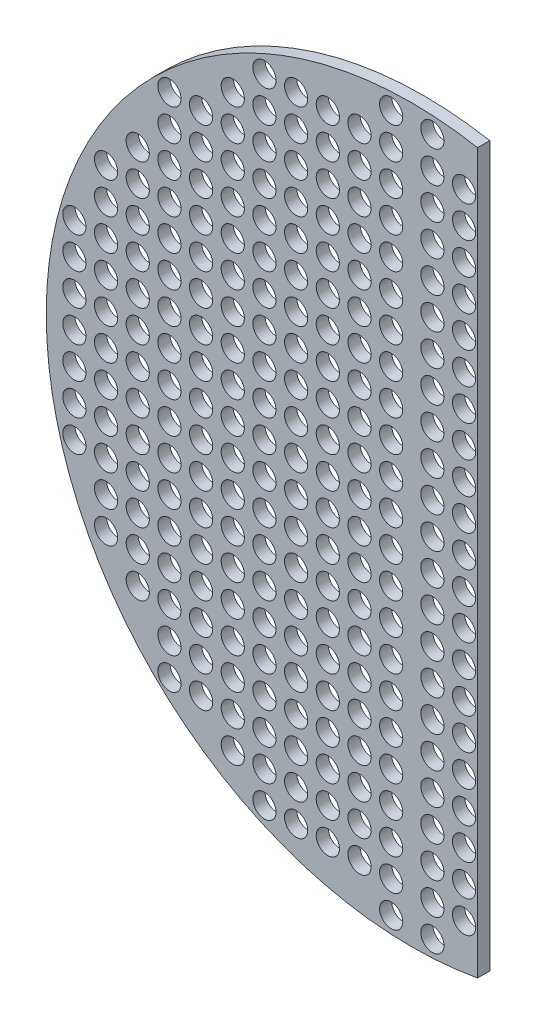
SolidWorks part; units mm, degrees
material " 12Х18Н10Т ГОСТ 4543-71"
ref_plane "Спереди" through (0, 0, 0) normal (0, 0, 1) x (1, 0, 0)
ref_plane "Сверху" through (0, 0, 0) normal (0, 1, 0) x (1, 0, 0)
ref_plane "Справа" through (0, 0, 0) normal (1, 0, 0) x (0, 0, -1)
sketch "Эскиз1" plane through (0, 0, 0) normal (0, 0, 1) x (1, 0, 0)
  circle A0 centre (0, 0) radius 300
  dimension "D1" = 600
extrude "Бобышка-Вытянуть1" add sketch "Эскиз1" along normal mid plane 10
sketch "Sketch1" plane through (0, 0, 5) normal (0, 0, 1) x (1, 0, 0)
  line L1 (0, 0) -> (0, -73.9638) construction
  line L2 (3.9158, 0) -> (0, 0) construction
  line L3 (0, 0) -> (29.9158, 0) construction
  circle A0 centre (16.9158, 0) radius 9.525
  circle A1 centre (42.9158, 0) radius 9.525
  circle A11 centre (42.9158, 0) radius 9.525
  circle A21 centre (42.9158, 26) radius 9.525
  circle A31 centre (42.9158, 52) radius 9.525
  circle A41 centre (42.9158, 78) radius 9.525
  circle A51 centre (42.9158, 104) radius 9.525
  circle A60 centre (16.9158, -286) radius 9.525
  circle A61 centre (42.9158, 130) radius 9.525
  circle A70 centre (16.9158, -260) radius 9.525
  circle A71 centre (42.9158, 156) radius 9.525
  circle A79 centre (16.9158, -234) radius 9.525
  circle A80 centre (16.9158, -208) radius 9.525
  circle A81 centre (42.9158, 182) radius 9.525
  circle A88 centre (16.9158, -182) radius 9.525
  circle A89 centre (16.9158, -156) radius 9.525
  circle A90 centre (16.9158, -130) radius 9.525
  circle A91 centre (42.9158, 208) radius 9.525
  circle A98 centre (16.9158, -104) radius 9.525
  circle A99 centre (16.9158, -78) radius 9.525
  circle A100 centre (16.9158, -52) radius 9.525
  circle A101 centre (42.9158, 234) radius 9.525
  circle A106 centre (16.9158, -26) radius 9.525
  circle A110 centre (42.9158, -260) radius 9.525
  circle A111 centre (42.9158, 260) radius 9.525
  circle A119 centre (42.9158, -234) radius 9.525
  circle A126 centre (42.9158, -208) radius 9.525
  circle A131 centre (16.9158, 26) radius 9.525
  circle A132 centre (16.9158, 52) radius 9.525
  circle A133 centre (16.9158, 78) radius 9.525
  circle A134 centre (16.9158, 104) radius 9.525
  circle A135 centre (16.9158, 130) radius 9.525
  circle A136 centre (16.9158, 156) radius 9.525
  circle A137 centre (16.9158, 182) radius 9.525
  circle A138 centre (16.9158, 208) radius 9.525
  circle A139 centre (16.9158, 234) radius 9.525
  circle A140 centre (16.9158, 260) radius 9.525
  circle A141 centre (16.9158, 286) radius 9.525
  circle A144 centre (42.9158, -182) radius 9.525
  circle A152 centre (42.9158, -156) radius 9.525
  circle A161 centre (42.9158, -130) radius 9.525
  circle A170 centre (42.9158, -104) radius 9.525
  circle A180 centre (42.9158, -78) radius 9.525
  circle A190 centre (42.9158, -52) radius 9.525
  circle A200 centre (42.9158, -26) radius 9.525
  circle A201 centre (-42.9158, -26) radius 9.525
  circle A202 centre (-68.9158, -26) radius 9.525
  circle A203 centre (-94.9158, -26) radius 9.525
  circle A204 centre (-120.9158, -26) radius 9.525
  circle A205 centre (-146.9158, -26) radius 9.525
  circle A206 centre (-172.9158, -26) radius 9.525
  circle A207 centre (-198.9158, -26) radius 9.525
  circle A208 centre (-224.9158, -26) radius 9.525
  circle A209 centre (-250.9158, -26) radius 9.525
  circle A210 centre (-276.9158, -26) radius 9.525
  circle A211 centre (-42.9158, -52) radius 9.525
  circle A212 centre (-68.9158, -52) radius 9.525
  circle A213 centre (-94.9158, -52) radius 9.525
  circle A214 centre (-120.9158, -52) radius 9.525
  circle A215 centre (-146.9158, -52) radius 9.525
  circle A216 centre (-172.9158, -52) radius 9.525
  circle A217 centre (-198.9158, -52) radius 9.525
  circle A218 centre (-224.9158, -52) radius 9.525
  circle A219 centre (-250.9158, -52) radius 9.525
  circle A220 centre (-276.9158, -52) radius 9.525
  circle A221 centre (-42.9158, -78) radius 9.525
  circle A222 centre (-68.9158, -78) radius 9.525
  circle A223 centre (-94.9158, -78) radius 9.525
  circle A224 centre (-120.9158, -78) radius 9.525
  circle A225 centre (-146.9158, -78) radius 9.525
  circle A226 centre (-172.9158, -78) radius 9.525
  circle A227 centre (-198.9158, -78) radius 9.525
  circle A228 centre (-224.9158, -78) radius 9.525
  circle A229 centre (-250.9158, -78) radius 9.525
  circle A230 centre (-276.9158, -78) radius 9.525
  circle A231 centre (-42.9158, -104) radius 9.525
  circle A232 centre (-68.9158, -104) radius 9.525
  circle A233 centre (-94.9158, -104) radius 9.525
  circle A234 centre (-120.9158, -104) radius 9.525
  circle A235 centre (-146.9158, -104) radius 9.525
  circle A236 centre (-172.9158, -104) radius 9.525
  circle A237 centre (-198.9158, -104) radius 9.525
  circle A238 centre (-224.9158, -104) radius 9.525
  circle A239 centre (-250.9158, -104) radius 9.525
  circle A240 centre (-42.9158, -130) radius 9.525
  circle A241 centre (-68.9158, -130) radius 9.525
  circle A242 centre (-94.9158, -130) radius 9.525
  circle A243 centre (-120.9158, -130) radius 9.525
  circle A244 centre (-146.9158, -130) radius 9.525
  circle A245 centre (-172.9158, -130) radius 9.525
  circle A246 centre (-198.9158, -130) radius 9.525
  circle A247 centre (-224.9158, -130) radius 9.525
  circle A248 centre (-250.9158, -130) radius 9.525
  circle A249 centre (-42.9158, -156) radius 9.525
  circle A250 centre (-68.9158, -156) radius 9.525
  circle A251 centre (-94.9158, -156) radius 9.525
  circle A252 centre (-120.9158, -156) radius 9.525
  circle A253 centre (-146.9158, -156) radius 9.525
  circle A254 centre (-172.9158, -156) radius 9.525
  circle A255 centre (-198.9158, -156) radius 9.525
  circle A256 centre (-224.9158, -156) radius 9.525
  circle A257 centre (-42.9158, -182) radius 9.525
  circle A258 centre (-68.9158, -182) radius 9.525
  circle A259 centre (-94.9158, -182) radius 9.525
  circle A260 centre (-16.9158, 286) radius 9.525
  circle A261 centre (-16.9158, 260) radius 9.525
  circle A262 centre (-16.9158, 234) radius 9.525
  circle A263 centre (-16.9158, 208) radius 9.525
  circle A264 centre (-16.9158, 182) radius 9.525
  circle A265 centre (-16.9158, 156) radius 9.525
  circle A266 centre (-16.9158, 130) radius 9.525
  circle A267 centre (-16.9158, 104) radius 9.525
  circle A268 centre (-16.9158, 78) radius 9.525
  circle A269 centre (-16.9158, 52) radius 9.525
  circle A270 centre (-16.9158, 26) radius 9.525
  circle A271 centre (-120.9158, -182) radius 9.525
  circle A272 centre (-146.9158, -182) radius 9.525
  circle A273 centre (-172.9158, -182) radius 9.525
  circle A274 centre (-198.9158, -182) radius 9.525
  circle A275 centre (-42.9158, -208) radius 9.525
  circle A276 centre (-68.9158, -208) radius 9.525
  circle A277 centre (-94.9158, -208) radius 9.525
  circle A278 centre (-120.9158, -208) radius 9.525
  circle A279 centre (-146.9158, -208) radius 9.525
  circle A280 centre (-172.9158, -208) radius 9.525
  circle A281 centre (-198.9158, -208) radius 9.525
  circle A282 centre (-42.9158, -234) radius 9.525
  circle A283 centre (-68.9158, -234) radius 9.525
  circle A284 centre (-94.9158, -234) radius 9.525
  circle A285 centre (-120.9158, -234) radius 9.525
  circle A286 centre (-146.9158, -234) radius 9.525
  circle A287 centre (-120.9158, 260) radius 9.525
  circle A288 centre (-94.9158, 260) radius 9.525
  circle A289 centre (-68.9158, 260) radius 9.525
  circle A290 centre (-42.9158, 260) radius 9.525
  circle A291 centre (-42.9158, -260) radius 9.525
  circle A292 centre (-68.9158, -260) radius 9.525
  circle A293 centre (-94.9158, -260) radius 9.525
  circle A294 centre (-120.9158, -260) radius 9.525
  circle A295 centre (-16.9158, -26) radius 9.525
  circle A296 centre (-146.9158, 234) radius 9.525
  circle A297 centre (-120.9158, 234) radius 9.525
  circle A298 centre (-94.9158, 234) radius 9.525
  circle A299 centre (-68.9158, 234) radius 9.525
  circle A300 centre (-42.9158, 234) radius 9.525
  circle A301 centre (-16.9158, -52) radius 9.525
  circle A302 centre (-16.9158, -78) radius 9.525
  circle A303 centre (-16.9158, -104) radius 9.525
  circle A304 centre (-198.9158, 208) radius 9.525
  circle A305 centre (-172.9158, 208) radius 9.525
  circle A306 centre (-146.9158, 208) radius 9.525
  circle A307 centre (-120.9158, 208) radius 9.525
  circle A308 centre (-94.9158, 208) radius 9.525
  circle A309 centre (-68.9158, 208) radius 9.525
  circle A310 centre (-42.9158, 208) radius 9.525
  circle A311 centre (-16.9158, -130) radius 9.525
  circle A312 centre (-16.9158, -156) radius 9.525
  circle A313 centre (-16.9158, -182) radius 9.525
  circle A314 centre (-198.9158, 182) radius 9.525
  circle A315 centre (-172.9158, 182) radius 9.525
  circle A316 centre (-146.9158, 182) radius 9.525
  circle A317 centre (-120.9158, 182) radius 9.525
  circle A318 centre (-94.9158, 182) radius 9.525
  circle A319 centre (-68.9158, 182) radius 9.525
  circle A320 centre (-42.9158, 182) radius 9.525
  circle A321 centre (-16.9158, -208) radius 9.525
  circle A322 centre (-16.9158, -234) radius 9.525
  circle A323 centre (-224.9158, 156) radius 9.525
  circle A324 centre (-198.9158, 156) radius 9.525
  circle A325 centre (-172.9158, 156) radius 9.525
  circle A326 centre (-146.9158, 156) radius 9.525
  circle A327 centre (-120.9158, 156) radius 9.525
  circle A328 centre (-94.9158, 156) radius 9.525
  circle A329 centre (-68.9158, 156) radius 9.525
  circle A330 centre (-42.9158, 156) radius 9.525
  circle A331 centre (-16.9158, -260) radius 9.525
  circle A332 centre (-250.9158, 130) radius 9.525
  circle A333 centre (-224.9158, 130) radius 9.525
  circle A334 centre (-198.9158, 130) radius 9.525
  circle A335 centre (-172.9158, 130) radius 9.525
  circle A336 centre (-146.9158, 130) radius 9.525
  circle A337 centre (-120.9158, 130) radius 9.525
  circle A338 centre (-94.9158, 130) radius 9.525
  circle A339 centre (-68.9158, 130) radius 9.525
  circle A340 centre (-42.9158, 130) radius 9.525
  circle A341 centre (-16.9158, -286) radius 9.525
  circle A342 centre (-250.9158, 104) radius 9.525
  circle A343 centre (-224.9158, 104) radius 9.525
  circle A344 centre (-198.9158, 104) radius 9.525
  circle A345 centre (-172.9158, 104) radius 9.525
  circle A346 centre (-146.9158, 104) radius 9.525
  circle A347 centre (-120.9158, 104) radius 9.525
  circle A348 centre (-94.9158, 104) radius 9.525
  circle A349 centre (-68.9158, 104) radius 9.525
  circle A350 centre (-42.9158, 104) radius 9.525
  circle A351 centre (-276.9158, 78) radius 9.525
  circle A352 centre (-250.9158, 78) radius 9.525
  circle A353 centre (-224.9158, 78) radius 9.525
  circle A354 centre (-198.9158, 78) radius 9.525
  circle A355 centre (-172.9158, 78) radius 9.525
  circle A356 centre (-146.9158, 78) radius 9.525
  circle A357 centre (-120.9158, 78) radius 9.525
  circle A358 centre (-94.9158, 78) radius 9.525
  circle A359 centre (-68.9158, 78) radius 9.525
  circle A360 centre (-42.9158, 78) radius 9.525
  circle A361 centre (-276.9158, 52) radius 9.525
  circle A362 centre (-250.9158, 52) radius 9.525
  circle A363 centre (-224.9158, 52) radius 9.525
  circle A364 centre (-198.9158, 52) radius 9.525
  circle A365 centre (-172.9158, 52) radius 9.525
  circle A366 centre (-146.9158, 52) radius 9.525
  circle A367 centre (-120.9158, 52) radius 9.525
  circle A368 centre (-94.9158, 52) radius 9.525
  circle A369 centre (-68.9158, 52) radius 9.525
  circle A370 centre (-42.9158, 52) radius 9.525
  circle A371 centre (-276.9158, 26) radius 9.525
  circle A372 centre (-250.9158, 26) radius 9.525
  circle A373 centre (-224.9158, 26) radius 9.525
  circle A374 centre (-198.9158, 26) radius 9.525
  circle A375 centre (-172.9158, 26) radius 9.525
  circle A376 centre (-146.9158, 26) radius 9.525
  circle A377 centre (-120.9158, 26) radius 9.525
  circle A378 centre (-94.9158, 26) radius 9.525
  circle A379 centre (-68.9158, 26) radius 9.525
  circle A380 centre (-42.9158, 26) radius 9.525
  circle A381 centre (-276.9158, 0) radius 9.525
  circle A382 centre (-250.9158, 0) radius 9.525
  circle A383 centre (-224.9158, 0) radius 9.525
  circle A384 centre (-198.9158, 0) radius 9.525
  circle A385 centre (-172.9158, 0) radius 9.525
  circle A386 centre (-146.9158, 0) radius 9.525
  circle A387 centre (-120.9158, 0) radius 9.525
  circle A388 centre (-94.9158, 0) radius 9.525
  circle A389 centre (-68.9158, 0) radius 9.525
  circle A390 centre (-42.9158, 0) radius 9.525
  circle A391 centre (-276.9158, 0) radius 9.525
  circle A392 centre (-250.9158, 0) radius 9.525
  circle A393 centre (-224.9158, 0) radius 9.525
  circle A394 centre (-198.9158, 0) radius 9.525
  circle A395 centre (-172.9158, 0) radius 9.525
  circle A396 centre (-146.9158, 0) radius 9.525
  circle A397 centre (-120.9158, 0) radius 9.525
  circle A398 centre (-94.9158, 0) radius 9.525
  circle A399 centre (-68.9158, 0) radius 9.525
  circle A400 centre (-42.9158, 0) radius 9.525
  circle A401 centre (-16.9158, 0) radius 9.525
sketch "Эскиз3" plane through (0, 0, 5) normal (0, 0, 1) x (1, 0, 0)
  line L0 (0, 405.6785) -> (0, -400.4859) construction
  line L1 (0, 0) -> (367.3561, 0) construction
  line L2 (54, 295.1) -> (54, -295.1)
  circle A1 centre (0, 0) radius 300 construction
  arc A2 (54, -295.1) -> (54, 295.1) centre (0, 0) ccw
  dimension "D1" = 300
  dimension "D2" = 54
extrude "Вырез-Вытянуть2" cut sketch "Эскиз3" against normal blind 10
extrude "Cut-Extrude1" cut sketch "Sketch1" against normal through all
